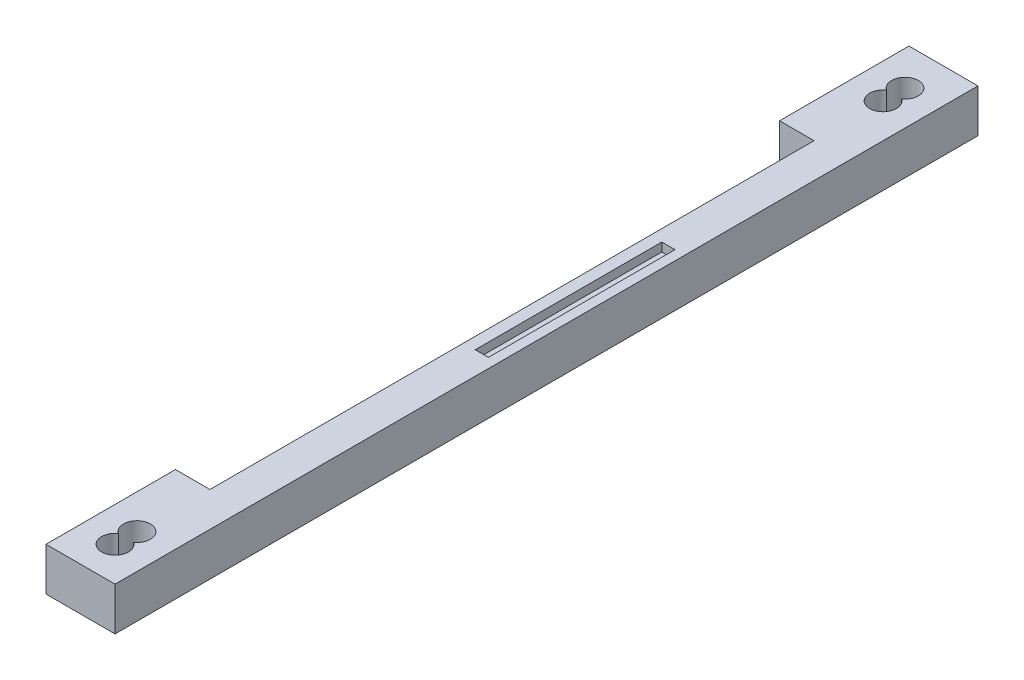
SolidWorks part; units mm, degrees
ref_plane "Ebene vorne" through (0, 0, 0) normal (0, 0, 1) x (1, 0, 0)
ref_plane "Ebene oben" through (0, 0, 0) normal (0, 1, 0) x (1, 0, 0)
ref_plane "Ebene rechts" through (0, 0, 0) normal (1, 0, 0) x (0, 0, -1)
sketch "Sketch1" plane through (0, 0, 0) normal (0, 1, 0) x (1, 0, 0)
  line L1 (-4, -50) -> (4, -50)
  line L2 (-4, -50) -> (-4, 50)
  line L3 (-4, 50) -> (4, 50)
  line L4 (4, -50) -> (4, 50)
  line L5 (-4, -50) -> (4, 50) construction
  line L6 (-4, 50) -> (4, -50) construction
  point P0 (0, 0)
  dimension "D1" = 8
  dimension "D2" = 100
extrude "Extrude1" add sketch "Sketch1" along normal blind 5
sketch "Sketch2" plane through (0, 5, 0) normal (0, 1, 0) x (1, 0, 0)
  line L1 (-4, -50) -> (4, -50) construction
  circle A0 centre (0, -46) radius 1.55
  dimension "D1" = 3.1
  dimension "D2" = 4
extrude "Extrude4" cut sketch "Sketch2" against normal blind 5
sketch "Sketch4" plane through (0, 5, 0) normal (0, 1, 0) x (1, 0, 0)
  circle A0 centre (0, -43.46) radius 1.55
  circle A1 centre (0, -46) radius 1.55 construction
  circle A2 centre (0, 43) radius 1.55
  circle A3 centre (0, 45.54) radius 1.55
  circle M2 centre (0, -46) radius 1.55
  dimension "D1" = 89
  dimension "D2" = 2.54
  dimension "D3" = 3.1
  dimension "D5" = 2.54
extrude "Extrude6" cut sketch "Sketch4" against normal blind 5 contours A0 M2 | A2 | A3
sketch "Sketch5" plane through (0, 5, 0) normal (0, 1, 0) x (1, 0, 0)
  line L0 (-4, 50) -> (-4, -50) construction
  line L1 (-4, 35) -> (0, 35)
  line L2 (-4, 35) -> (-4, -35)
  line L3 (-4, -35) -> (0, -35)
  line L4 (0, 35) -> (0, -35)
  line L5 (4, 50) -> (-4, 50) construction
  dimension "D1" = 70
  dimension "D2" = 4
  dimension "D3" = 15
extrude "Extrude7" cut sketch "Sketch5" against normal blind 5
sketch "Sketch6" plane through (0, 5, 0) normal (0, 1, 0) x (1, 0, 0)
  line L1 (2.8779, -5.6079) -> (1.3474, -5.6079)
  line L2 (2.8779, -5.6079) -> (2.8779, 16.0106)
  line L3 (2.8779, 16.0106) -> (1.3474, 16.0106)
  line L4 (1.3474, -5.6079) -> (1.3474, 16.0106)
extrude "Extrude8" cut sketch "Sketch6" against normal blind 1
